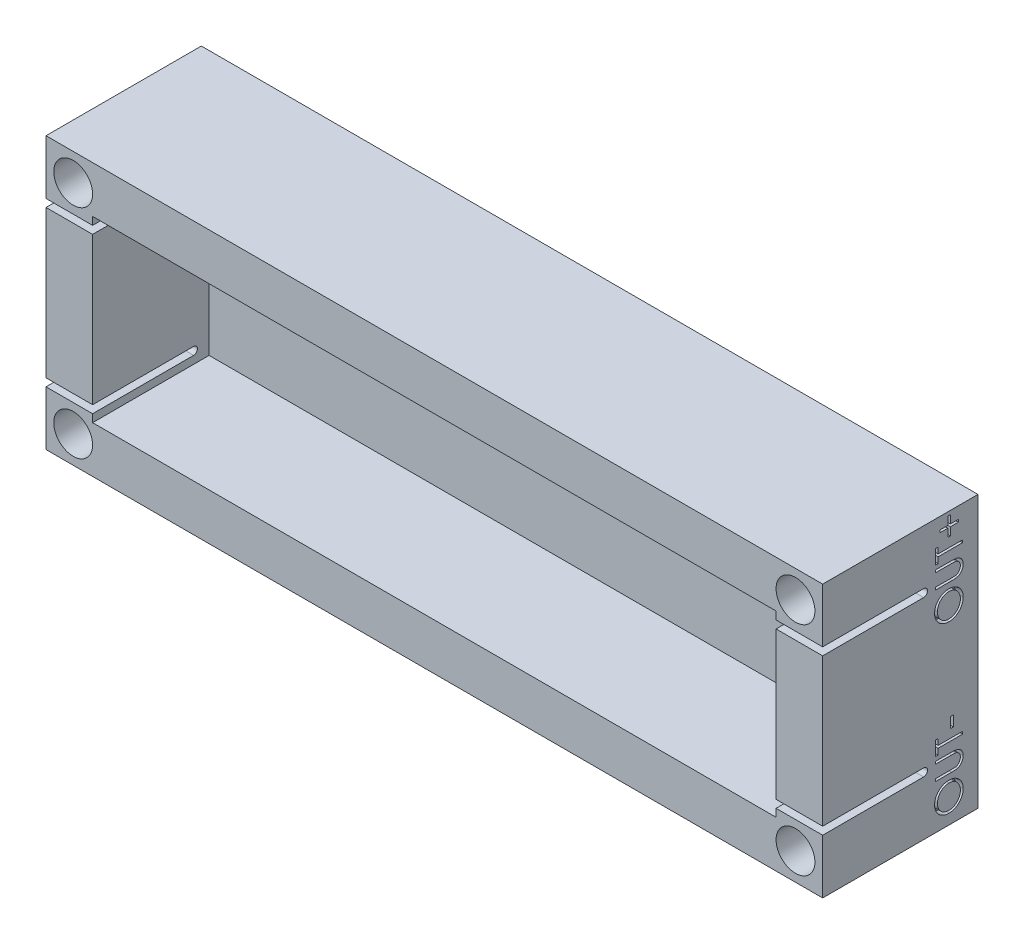
SolidWorks part; units mm, degrees
ref_plane "Front Plane" through (0, 0, 0) normal (0, 0, 1) x (1, 0, 0)
ref_plane "Top Plane" through (0, 0, 0) normal (0, 1, 0) x (1, 0, 0)
ref_plane "Right Plane" through (0, 0, 0) normal (1, 0, 0) x (0, 0, -1)
sketch "Sketch1" plane through (0, 0, 0) normal (0, 0, 1) x (1, 0, 0)
  line L1 (-50, 17.5) -> (50, 17.5)
  line L2 (-50, 17.5) -> (-50, -17.5)
  line L3 (-50, -17.5) -> (50, -17.5)
  line L4 (50, 17.5) -> (50, -17.5)
  line L5 (-50, 17.5) -> (50, -17.5) construction
  line L6 (-50, -17.5) -> (50, 17.5) construction
  point P0 (0, 0)
  dimension "D1" = 100
  dimension "D2" = 35
extrude "Boss-Extrude1" add sketch "Sketch1" along normal blind 5
sketch "Sketch2" plane through (0, 0, 5) normal (0, 0, 1) x (1, 0, 0)
  line L1 (50, 17.5) -> (-50, 17.5)
  line L2 (50, 17.5) -> (50, -17.5)
  line L3 (50, -17.5) -> (-50, -17.5)
  line L4 (-50, 17.5) -> (-50, -17.5)
  line L5 (50, 17.5) -> (-50, -17.5) construction
  line L6 (50, -17.5) -> (-50, 17.5) construction
  line L7 (44, 11.5) -> (-44, 11.5)
  line L8 (44, 11.5) -> (44, -11.5)
  line L9 (44, -11.5) -> (-44, -11.5)
  line L10 (-44, 11.5) -> (-44, -11.5)
  line L11 (44, 11.5) -> (-44, -11.5) construction
  line L12 (44, -11.5) -> (-44, 11.5) construction
  point P0 (0, 0)
  point P7 (0, 0)
  dimension "D1" = 6
  dimension "D2" = 6
extrude "Boss-Extrude2" add sketch "Sketch2" along normal blind 15
sketch "Sketch3" plane through (-50, 0, 0) normal (-1, 0, 0) x (0, 0, 1)
  line L0 (20, 10) -> (7, 10) construction
  line L1 (20, 17.5) -> (20, -17.5) construction
  line L2 (20, 9.5) -> (7, 9.5)
  line L3 (20, 10.5) -> (7, 10.5)
  line L4 (20, -10) -> (7, -10) construction
  line L5 (20, -10.5) -> (7, -10.5)
  line L6 (20, -9.5) -> (7, -9.5)
  line L7 (20, 17.5) -> (0, 17.5) construction
  line L8 (20, -17.5) -> (0, -17.5) construction
  line L9 (0, 17.5) -> (0, -17.5) construction
  arc A0 (20, 9.5) -> (20, 10.5) centre (20, 10) ccw
  arc A1 (7, 10.5) -> (7, 9.5) centre (7, 10) ccw
  arc A2 (20, -10.5) -> (20, -9.5) centre (20, -10) ccw
  arc A3 (7, -9.5) -> (7, -10.5) centre (7, -10) ccw
  point P4 (13.5, 10)
  point P11 (13.5, -10)
  point P16 (0, 0)
  dimension "D1" = 0.5
  dimension "D2" = 0.5
  dimension "D3" = 7.5
  dimension "D4" = 7.5
  dimension "D5" = 7
extrude "Cut-Extrude1" cut sketch "Sketch3" against normal through all
sketch "Sketch4" plane through (-50, 0, 0) normal (-1, 0, 0) x (0, 0, 1)
  line L0 (2, 13.031) -> (2, 4.8113) construction
  line L1 (2, -7.4798) -> (2, -16.0296) construction
  line L2 (0, 17.5) -> (0, -17.5) construction
  text T0 "IN+"
  text T1 "IN-"
  point P3 (1.4301, 14.8981)
  point P6 (1.3547, -16.0296)
  point P7 (1.5056, -9.0143)
  point P8 (1.4301, -10.1835)
  point P11 (2, 13.031)
  point P12 (2, -6.9681)
  point P13 (0, 0)
  point P14 (2, -7.4798)
  dimension "D1" = 2
extrude "Cut-Extrude2" cut sketch "Sketch4" against normal blind 1
sketch "Sketch5" plane through (50, 0, 0) normal (1, 0, 0) x (0, 0, -1)
  line L0 (-2, -16.4445) -> (-2, -5.7707) construction
  line L1 (-2, 4.9032) -> (-2, 16.6708) construction
  line L2 (0, -17.5) -> (0, 17.5) construction
  text T0 "OUT-"
  text T1 "OUT+"
  point P4 (-1.9187, 6.5196)
  point P5 (-1.9536, -2.2662)
  point P6 (-1.849, -14.4338)
  point P8 (-1.9187, 4.2186)
  point P9 (-1.6398, 14.5384)
  point P10 (-1.5433, -15.9165)
  point P11 (-1.6049, 2.2662)
  point P12 (-1.5056, 16.6708)
  point P13 (-1.5056, 4.9032)
  point P14 (-1.5056, -16.4445)
  point P15 (-1.7319, -5.7707)
  dimension "D1" = 2
extrude "Cut-Extrude3" cut sketch "Sketch5" against normal blind 1
sketch "Sketch6" plane through (0, 0, 20) normal (0, 0, 1) x (1, 0, 0)
  line L0 (50, 17.5) -> (-50, 17.5) construction
  line L1 (-50, 17.5) -> (-50, 10.5) construction
  line L2 (-50, -17.5) -> (50, -17.5) construction
  line L3 (-50, -10.5) -> (-50, -17.5) construction
  line L4 (50, 10.5) -> (50, 17.5) construction
  circle A0 centre (-46.5, 14) radius 2.5
  circle A1 centre (-46.5, -14) radius 2.5
  circle A2 centre (46.5, 14) radius 2.5
  circle A3 centre (46.5, -14) radius 2.5
  point P18 (0, 0)
  point P19 (0, 0)
  point P20 (0, 0)
  dimension "D1" = 5
  dimension "D4" = 5
  dimension "D7" = 5
  dimension "D10" = 5
  dimension "D2" = 3.5
  dimension "D3" = 3.5
  dimension "D5" = 3.5
  dimension "D6" = 3.5
  dimension "D8" = 3.5
  dimension "D9" = 3.5
extrude "Cut-Extrude4" cut sketch "Sketch6" against normal blind 5
